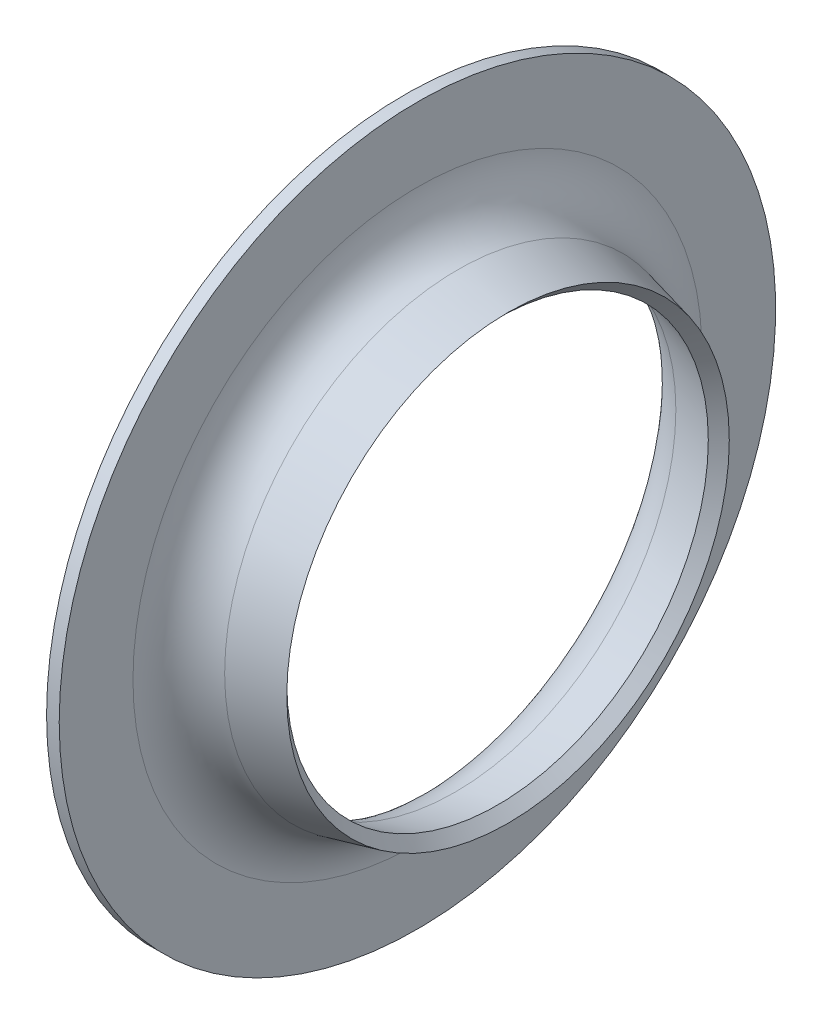
SolidWorks part; units mm, degrees
ref_plane "前视基准面" through (0, 0, 0) normal (0, 0, 1) x (1, 0, 0)
ref_plane "上视基准面" through (0, 0, 0) normal (0, 1, 0) x (1, 0, 0)
ref_plane "右视基准面" through (0, 0, 0) normal (1, 0, 0) x (0, 0, -1)
sketch "草图1" plane through (0, 0, 0) normal (0, 0, 1) x (1, 0, 0)
  line L0 (-48.7456, 0) -> (26.441, 0) construction
  line L1 (0, 37.122) -> (0, -32.0957) construction
  line L2 (-4.3, 17) -> (-4.3, 13.5)
  line L3 (-2.3805, 11.0683) -> (0, 10.5)
  line L4 (-4.9, 17) -> (-4.9, 13.5)
  line L5 (-2.5199, 10.4847) -> (-0.498, 10.002)
  line L6 (-4.9, 17) -> (-4.3, 17)
  line L7 (0, 10.5) -> (-0.498, 10.002)
  line L9 (-2.5199, 10.4847) -> (-0.1393, 9.9164) construction
  arc A0 (-2.3805, 11.0683) -> (-4.3, 13.5) centre (-1.8, 13.5) cw
  arc A1 (-2.5199, 10.4847) -> (-4.9, 13.5) centre (-1.8, 13.5) cw
  dimension "D5" = 2.5
  dimension "D1" = 21
  dimension "D2" = 4.3
  dimension "D3" = 34
  dimension "D4" = 27
  dimension "D6" = 2.4474
  dimension "D8" = 45
  dimension "D7" = 0.6
revolve "旋转1" add sketch "草图1" angle 360 about L0
